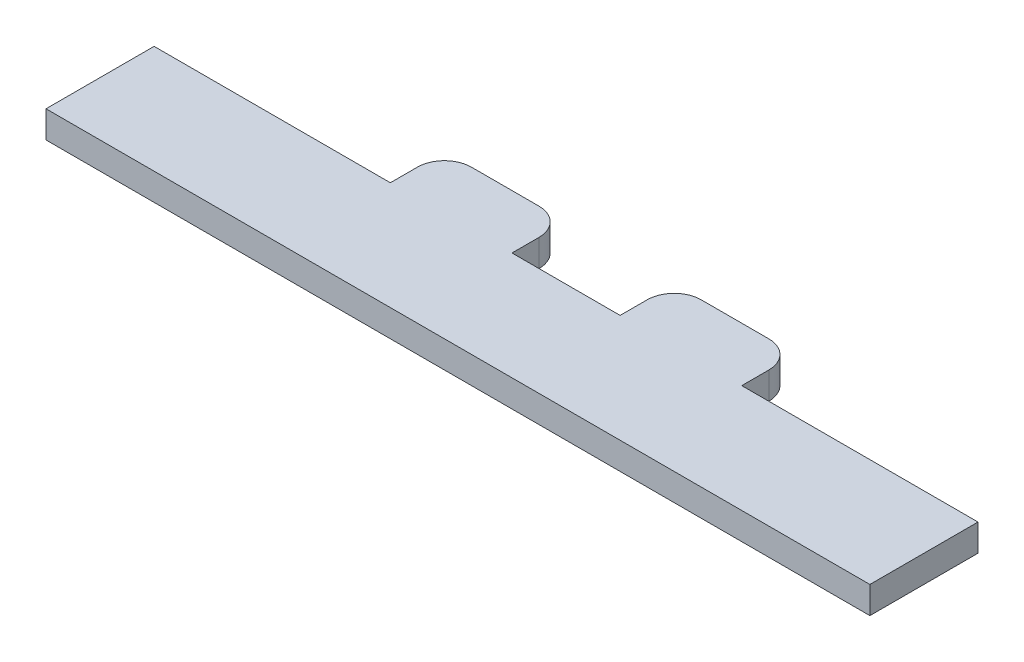
SolidWorks part; units mm, degrees
material "Cedar"
ref_plane "Front Plane" through (0, 0, 0) normal (0, 0, 1) x (1, 0, 0)
ref_plane "Top Plane" through (0, 0, 0) normal (0, 1, 0) x (1, 0, 0)
ref_plane "Right Plane" through (0, 0, 0) normal (1, 0, 0) x (0, 0, -1)
sketch "Sketch1" plane through (0, 0, 0) normal (0, 1, 0) x (1, 0, 0)
  line L0 (0, 44.0455) -> (0, -33.4746) construction
  line L1 (0, -55) -> (0, 55) construction
  line L2 (-20, 20) -> (-20, 40)
  line L3 (-152.4, 20) -> (152.4, 20)
  line L4 (-152.4, 20) -> (-152.4, -20)
  line L5 (-152.4, -20) -> (152.4, -20)
  line L6 (152.4, 20) -> (152.4, -20)
  line L7 (-152.4, 20) -> (152.4, -20) construction
  line L8 (-152.4, -20) -> (152.4, 20) construction
  line L9 (20, 20) -> (-20, 20)
  line L13 (-20, 40) -> (-65, 40)
  line L14 (65, 40) -> (65, 20)
  line L15 (-65, 40) -> (-65, 20)
  line L16 (20, 20) -> (20, 40)
  line L17 (20, 40) -> (65, 40)
  point P5 (0, 0)
  dimension "D1" = 40
  dimension "D2" = 20
  dimension "D3" = 304.8
  dimension "D4" = 40
  dimension "D5" = 45
extrude "Boss-Extrude1" add sketch "Sketch1" along normal blind 10 contours L13 L15 L3 L2 | L17 L16 L3 L14 | L6 L3 L4 L5
fillet "Fillet1" radius 10 4 edges at (-65, 5, -40) (65, 5, -40) (20, 5, -40) (-20, 5, -40)
